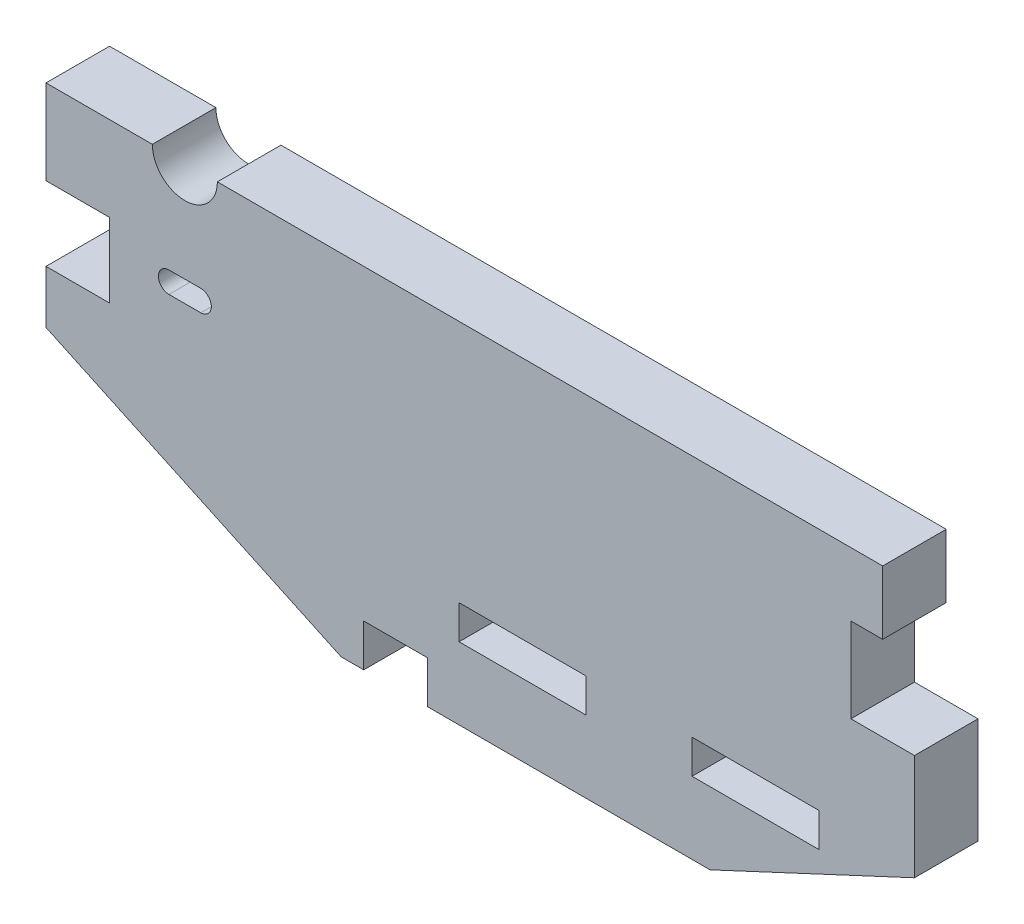
SolidWorks part; units mm, degrees
material "Plywood"
ref_plane "Plan de face" through (0, 0, 0) normal (0, 0, 1) x (1, 0, 0)
ref_plane "Plan de dessus" through (0, 0, 0) normal (0, 1, 0) x (1, 0, 0)
ref_plane "Plan de droite" through (0, 0, 0) normal (1, 0, 0) x (0, 0, -1)
sketch "Esquisse1" plane through (0, 0, 0) normal (0, 0, 1) x (1, 0, 0)
  line L1 (0, 0) -> (82, 0)
  line L2 (0, 0) -> (0, 33)
  line L3 (0, 33) -> (82, 33)
  line L4 (82, 0) -> (82, 33)
  dimension "D1" = 33
  dimension "D2" = 82
extrude "Boss.-Extru.1" add sketch "Esquisse1" along normal blind 6
sketch "Esquisse2" plane through (0, 0, 6) normal (0, 0, 1) x (1, 0, 0)
  line L0 (82, 33) -> (79, 33)
  line L1 (82, 33) -> (0, 33) construction
  line L2 (79, 33) -> (79, 27)
  line L3 (79, 27) -> (76, 27)
  line L4 (76, 27) -> (76, 19)
  line L5 (76, 19) -> (82, 19)
  line L6 (82, 0) -> (82, 33) construction
  line L7 (82, 19) -> (82, 33)
  dimension "D1" = 3
  dimension "D2" = 3
  dimension "D3" = 6
  dimension "D4" = 8
extrude "Enlèv. mat.-Extru.1" cut sketch "Esquisse2" against normal blind 10
sketch "Esquisse3" plane through (0, 0, 6) normal (0, 0, 1) x (1, 0, 0)
  line L0 (0, 33) -> (0, 0) construction
  line L1 (0, 25) -> (6, 25)
  line L2 (0, 25) -> (0, 18)
  line L3 (0, 18) -> (6, 18)
  line L4 (6, 25) -> (6, 18)
  line L5 (79, 33) -> (0, 33) construction
  dimension "D1" = 6
  dimension "D2" = 7
  dimension "D3" = 8
extrude "Enlèv. mat.-Extru.2" cut sketch "Esquisse3" against normal through all
chamfer "Chanfrein1" distance 13 angle 65 1 edges at (0, 0, 3)
chamfer "Chanfrein2" distance 9 angle 65 1 edges at (82, 0, 3)
sketch "Esquisse4" plane through (0, 0, 6) normal (0, 0, 1) x (1, 0, 0)
  line L0 (36, 10) -> (76, 10) construction
  line L1 (39, 10) -> (51, 10)
  line L2 (39, 10) -> (39, 6.8)
  line L3 (39, 6.8) -> (51, 6.8)
  line L4 (51, 10) -> (51, 6.8)
  line L6 (61, 10) -> (73, 10)
  line L7 (61, 10) -> (61, 6.8)
  line L8 (61, 6.8) -> (73, 6.8)
  line L9 (73, 10) -> (73, 6.8)
  point P10 (39, 8.4)
  dimension "D1" = 3.2
  dimension "D2" = 3
  dimension "D3" = 3
  dimension "D4" = 12
  dimension "D5" = 12
extrude "Enlèv. mat.-Extru.3" cut sketch "Esquisse4" against normal blind 10
sketch "Esquisse5" plane through (0, 0, 6) normal (0, 0, 1) x (1, 0, 0)
  line L0 (447.8098, 61.9949) -> (447.8098, 59.9949) construction
  line L1 (448.8098, 61.9949) -> (448.8098, 59.9949)
  line L2 (446.8098, 61.9949) -> (446.8098, 59.9949)
  line L3 (441.8098, 61.9949) -> (441.8098, 59.9949) construction
  line L4 (442.8098, 61.9949) -> (442.8098, 59.9949)
  line L5 (440.8098, 61.9949) -> (440.8098, 59.9949)
  line L6 (441.8098, 86.9949) -> (441.8098, 84.9949) construction
  line L7 (442.8098, 86.9949) -> (442.8098, 84.9949)
  line L8 (440.8098, 86.9949) -> (440.8098, 84.9949)
  line L9 (441.8098, 111.9949) -> (441.8098, 109.9949) construction
  line L10 (442.8098, 111.9949) -> (442.8098, 109.9949)
  line L11 (440.8098, 111.9949) -> (440.8098, 109.9949)
  line L12 (441.8098, 136.9949) -> (441.8098, 134.9949) construction
  line L13 (442.8098, 136.9949) -> (442.8098, 134.9949)
  line L14 (440.8098, 136.9949) -> (440.8098, 134.9949)
  line L15 (447.8098, 86.9949) -> (447.8098, 84.9949) construction
  line L16 (448.8098, 86.9949) -> (448.8098, 84.9949)
  line L17 (446.8098, 86.9949) -> (446.8098, 84.9949)
  line L18 (447.8098, 111.9949) -> (447.8098, 109.9949) construction
  line L19 (448.8098, 111.9949) -> (448.8098, 109.9949)
  line L20 (446.8098, 111.9949) -> (446.8098, 109.9949)
  line L21 (447.8098, 136.9949) -> (447.8098, 134.9949) construction
  line L22 (448.8098, 136.9949) -> (448.8098, 134.9949)
  line L23 (446.8098, 136.9949) -> (446.8098, 134.9949)
  line L24 (11.6103, 22.5091) -> (14.6103, 22.5091) construction
  line L25 (11.6103, 23.5091) -> (14.6103, 23.5091)
  line L26 (11.6103, 21.5091) -> (14.6103, 21.5091)
  line L27 (79, 33) -> (0, 33) construction
  arc A0 (448.8098, 61.9949) -> (446.8098, 61.9949) centre (447.8098, 61.9949) ccw
  arc A1 (446.8098, 59.9949) -> (448.8098, 59.9949) centre (447.8098, 59.9949) ccw
  arc A2 (442.8098, 61.9949) -> (440.8098, 61.9949) centre (441.8098, 61.9949) ccw
  arc A3 (440.8098, 59.9949) -> (442.8098, 59.9949) centre (441.8098, 59.9949) ccw
  arc A4 (442.8098, 86.9949) -> (440.8098, 86.9949) centre (441.8098, 86.9949) ccw
  arc A5 (440.8098, 84.9949) -> (442.8098, 84.9949) centre (441.8098, 84.9949) ccw
  arc A6 (442.8098, 111.9949) -> (440.8098, 111.9949) centre (441.8098, 111.9949) ccw
  arc A7 (440.8098, 109.9949) -> (442.8098, 109.9949) centre (441.8098, 109.9949) ccw
  arc A8 (442.8098, 136.9949) -> (440.8098, 136.9949) centre (441.8098, 136.9949) ccw
  arc A9 (440.8098, 134.9949) -> (442.8098, 134.9949) centre (441.8098, 134.9949) ccw
  arc A10 (448.8098, 86.9949) -> (446.8098, 86.9949) centre (447.8098, 86.9949) ccw
  arc A11 (446.8098, 84.9949) -> (448.8098, 84.9949) centre (447.8098, 84.9949) ccw
  arc A12 (448.8098, 111.9949) -> (446.8098, 111.9949) centre (447.8098, 111.9949) ccw
  arc A13 (446.8098, 109.9949) -> (448.8098, 109.9949) centre (447.8098, 109.9949) ccw
  arc A14 (448.8098, 136.9949) -> (446.8098, 136.9949) centre (447.8098, 136.9949) ccw
  arc A15 (446.8098, 134.9949) -> (448.8098, 134.9949) centre (447.8098, 134.9949) ccw
  arc A16 (11.6103, 23.5091) -> (11.6103, 21.5091) centre (11.6103, 22.5091) ccw
  arc A17 (14.6103, 21.5091) -> (14.6103, 23.5091) centre (14.6103, 22.5091) ccw
  circle A18 centre (13.1103, 33) radius 3.07
  point P2 (447.8098, 60.9949)
  point P7 (447.8098, 62.9949)
  point P10 (441.8098, 60.9949)
  point P17 (441.8098, 85.9949)
  point P24 (441.8098, 110.9949)
  point P31 (441.8098, 135.9949)
  point P38 (447.8098, 85.9949)
  point P45 (447.8098, 110.9949)
  point P52 (447.8098, 135.9949)
  point P59 (13.1103, 22.5091)
  point P68 (13.1103, 30)
  dimension "D4" = 1
  dimension "D1" = 2
  dimension "D2" = 1
  dimension "D3" = 3
extrude "Enlèv. mat.-Extru.4" cut sketch "Esquisse5" against normal blind 10
sketch "Esquisse6" plane through (0, 0, 6) normal (0, 0, 1) x (1, 0, 0)
  line L1 (30, -5) -> (36, -5)
  line L2 (30, -5) -> (30, 4)
  line L3 (30, 4) -> (36, 4)
  line L4 (36, -5) -> (36, 4)
  line L6 (27.8786, 0) -> (62.6994, 0) construction
  point P6 (0, 0)
  point P9 (0, 0)
  dimension "D1" = 4
extrude "Enlèv. mat.-Extru.5" cut sketch "Esquisse6" against normal through all
